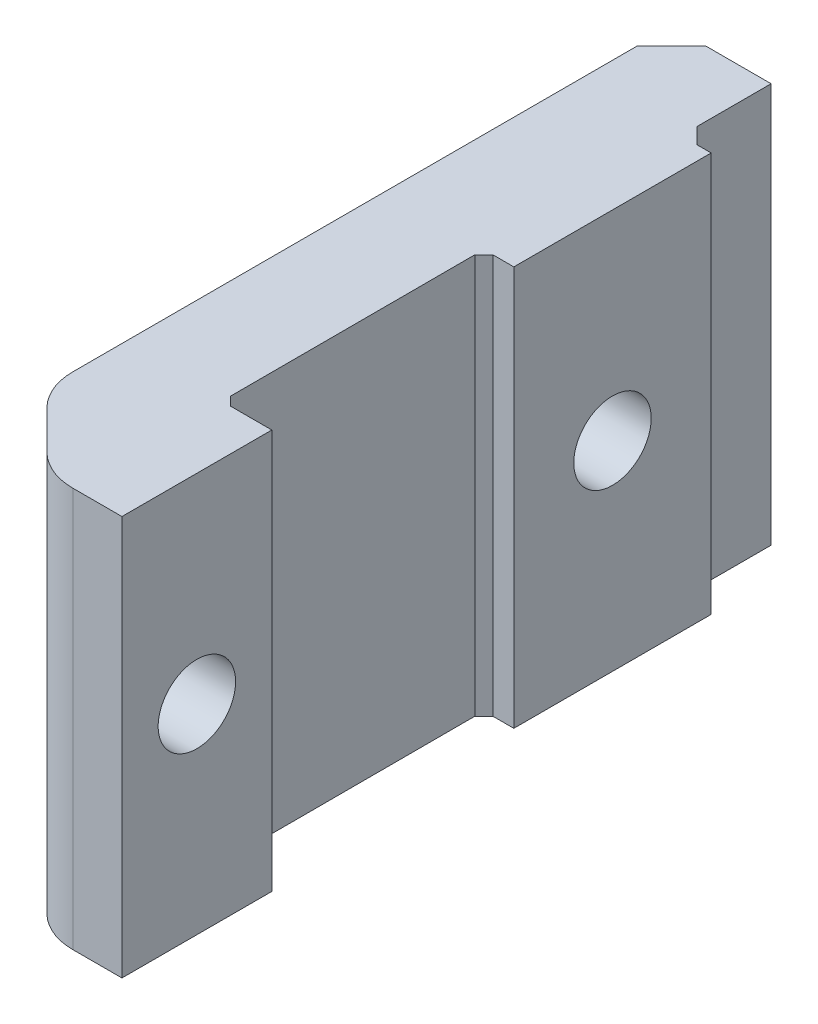
SolidWorks part; units mm, degrees
ref_plane "正面" through (0, 0, 0) normal (0, 0, 1) x (1, 0, 0)
ref_plane "平面" through (0, 0, 0) normal (0, 1, 0) x (1, 0, 0)
ref_plane "右側面" through (0, 0, 0) normal (1, 0, 0) x (0, 0, -1)
sketch "ｽｹｯﾁ1" plane through (0, 0, 0) normal (0, 1, 0) x (1, 0, 0)
  line L0 (1.3121, 19.972) -> (0.0562, 19.972)
  line L2 (-2.6769, 17.239) -> (-2.6769, -3.997)
  line L3 (-1.9446, -5.7647) -> (-0.4136, -7.2957)
  line L4 (1.3541, -8.028) -> (3.3231, -8.028)
  line L5 (3.3231, -8.028) -> (3.3231, -2.028)
  line L6 (3.3231, -2.028) -> (1.6762, -2.028)
  line L10 (2.5277, 8.472) -> (2.5121, 8.472)
  line L11 (2.5121, 8.472) -> (2.5121, 16.372)
  line L14 (1.3121, 16.9969) -> (1.3121, 19.972)
  line L15 (2.5121, 8.472) -> (1.6762, 8.472)
  line L18 (1.6762, -2.028) -> (1.3231, -1.6749)
  line L20 (1.3121, 16.9969) -> (1.9369, 16.372)
  line L21 (1.9369, 16.372) -> (2.5121, 16.372)
  line L22 (1.6762, 8.472) -> (1.3121, 8.108)
  line L23 (1.3121, 8.108) -> (1.3231, -1.6749)
  line L24 (-2.6769, 17.239) -> (-2.6769, 18.5991)
  line L25 (-2.6769, 18.5991) -> (-1.3039, 19.972)
  line L26 (-1.3039, 19.972) -> (0.0562, 19.972)
  arc A0 (1.3541, -8.028) -> (-0.4136, -7.2957) centre (1.3541, -5.528) cw
  arc A1 (-1.9446, -5.7647) -> (-2.6769, -3.997) centre (-0.1769, -3.997) cw
  point P20 (-1.3039, 19.972)
  dimension "D7" = 2.5
  dimension "D1" = 28
  dimension "D2" = 6
  dimension "D3" = 10.5
  dimension "D4" = 6
  dimension "D5" = 7.9
  dimension "D6" = 1.2
extrude "ﾎﾞｽ - 押し出し1" add sketch "ｽｹｯﾁ1" along normal blind 16 contours A1 L3 A0 L4 L5 L6 L18 L23 L22 L15 L11 L21 L20 L14 L0 L26 L25 L24 L2
sketch "ｽｹｯﾁ2" plane through (2.5121, 0, 0) normal (1, 0, 0) x (0, 0, -1)
  line L0 (-8.028, 16) -> (-8.028, 0) construction
  circle A0 centre (12.422, 8) radius 1.55
  circle A1 centre (-5.028, 8) radius 1.55
  dimension "D1" = 3
extrude "ｶｯﾄ - 押し出し1" cut sketch "ｽｹｯﾁ2" against normal through all both and the other way through all contours A0 | A1
